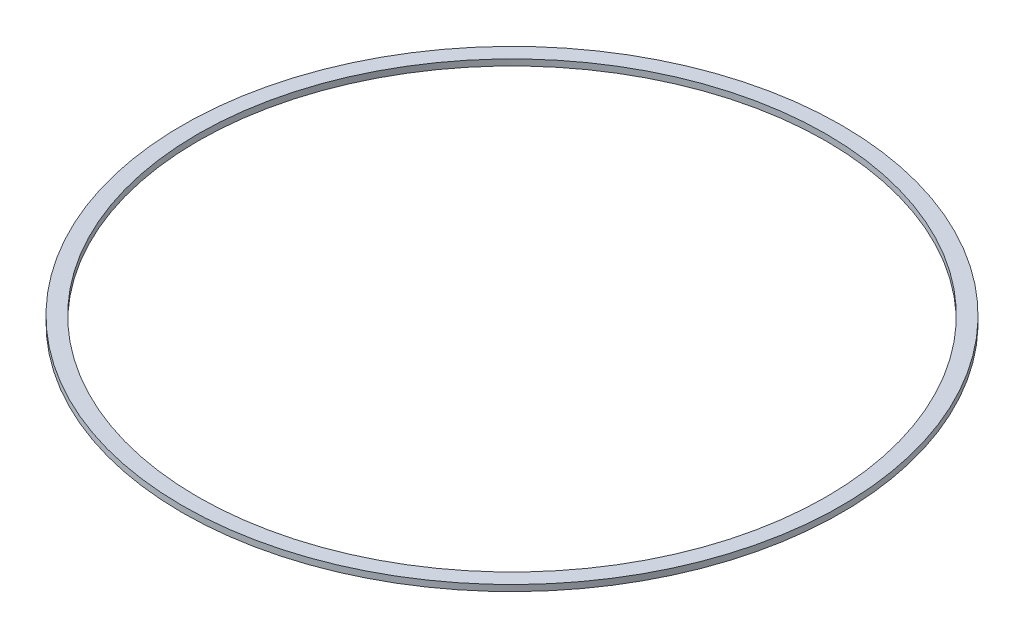
SolidWorks part; units mm, degrees
ref_plane "Front Plane" through (0, 0, 0) normal (0, 0, 1) x (1, 0, 0)
ref_plane "Top Plane" through (0, 0, 0) normal (0, 1, 0) x (1, 0, 0)
ref_plane "Right Plane" through (0, 0, 0) normal (1, 0, 0) x (0, 0, -1)
sketch "Sketch1" plane through (0, 0, 0) normal (0, 1, 0) x (1, 0, 0)
  circle A0 centre (0, 0) radius 136.525
  circle A1 centre (0, 0) radius 130.175
  dimension "D1" = 273.05
  dimension "D2" = 6.35
extrude "Boss-Extrude1" add sketch "Sketch1" along normal blind 2.54
